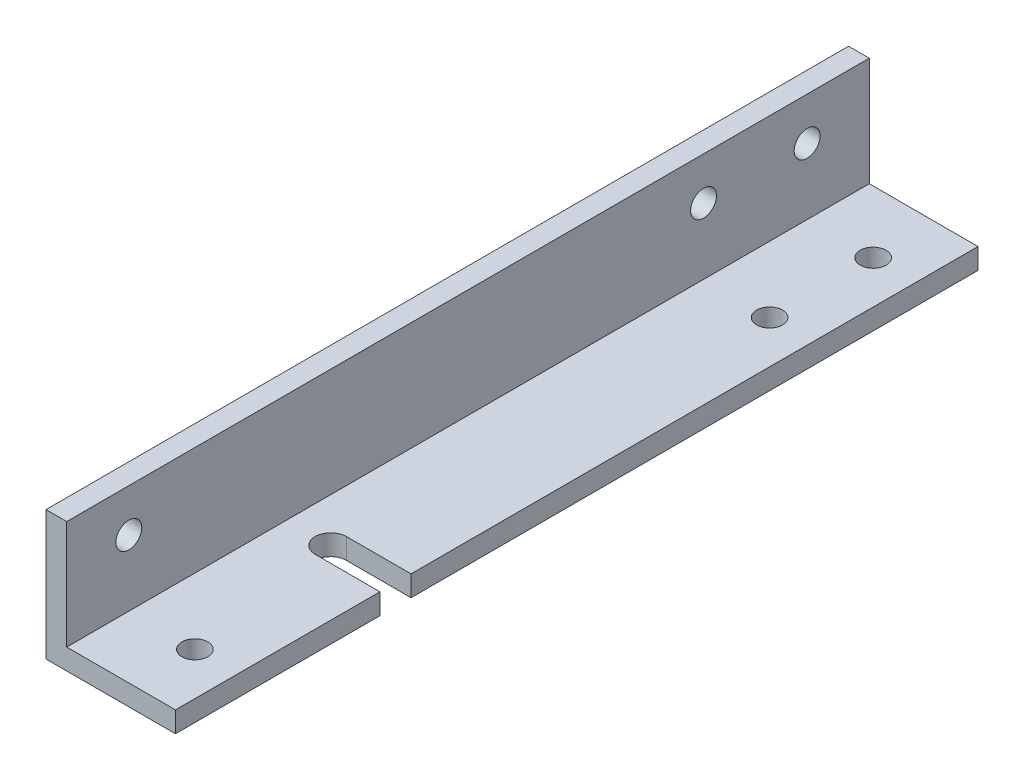
SolidWorks part; units mm, degrees
ref_plane "前视基准面" through (0, 0, 0) normal (0, 0, 1) x (1, 0, 0)
ref_plane "上视基准面" through (0, 0, 0) normal (0, 1, 0) x (1, 0, 0)
ref_plane "右视基准面" through (0, 0, 0) normal (1, 0, 0) x (0, 0, -1)
sketch "草图1" plane through (0, 0, 0) normal (0, 0, 1) x (1, 0, 0)
  line L0 (0, 25) -> (0, 0)
  line L1 (0, 0) -> (25, 0)
  line L2 (25, 0) -> (25, 4)
  line L3 (25, 4) -> (4, 4)
  line L4 (4, 4) -> (4, 25)
  line L5 (4, 25) -> (0, 25)
  dimension "D1" = 4
  dimension "D2" = 25
extrude "凸台-拉伸1" add sketch "草图1" along normal blind 155
hole_wizard "M6 螺纹孔1" positions "草图2" profile "草图3" tap size "M6" standard "GB" end condition through all
sketch "草图2" plane through (0, 4, 0) normal (0, 1, 0) x (1, 0, 0)
  line L0 (25, -155) -> (25, 0) construction
  line L1 (25, -155) -> (4, -155) construction
  line L2 (25, 0) -> (4, 0) construction
  line L3 (16.75, -12) -> (16.75, -32) construction
  point P0 (16.75, -12)
  point P2 (16.75, -143)
  point P12 (16.75, -32)
  dimension "D1" = 8.25
  dimension "D2" = 12
  dimension "D3" = 12
  dimension "D4" = 20
sketch "草图3" plane through (16.75, 4, 12) normal (1, 0, 0) x (0, 0, 1)
  line L0 (0, 0) -> (0, 4)
  line L1 (0, 4) -> (2.5, 4)
  line L2 (2.5, 4) -> (2.5, 0)
  line L5 (2.5, 0) -> (0, 0)
  line L11 (0, -6.35) -> (0, 107.95) construction
  dimension "通孔螺纹孔钻头直径" = 5
  dimension "通孔螺纹孔钻头深度" = 4
hole_wizard "M6 螺纹孔2" positions "草图4" profile "草图5" tap size "M6" standard "GB" end condition through all
sketch "草图4" plane through (4, 0, 0) normal (1, 0, 0) x (0, 0, -1)
  line L0 (-155, 25) -> (0, 25) construction
  line L1 (-155, 4) -> (-155, 25) construction
  line L2 (0, 4) -> (0, 25) construction
  line L3 (-32, 16.75) -> (-12, 16.75) construction
  point P0 (-143, 16.75)
  point P2 (-12, 16.75)
  point P12 (-32, 16.75)
  dimension "D1" = 8.25
  dimension "D2" = 12
  dimension "D3" = 12
  dimension "D4" = 20
sketch "草图5" plane through (4, 16.75, 143) normal (0, 1, 0) x (0, 0, -1)
  line L0 (0, 0) -> (0, 4)
  line L1 (0, 4) -> (2.5, 4)
  line L2 (2.5, 4) -> (2.5, 0)
  line L5 (2.5, 0) -> (0, 0)
  line L11 (0, -6.35) -> (0, 107.95) construction
  dimension "通孔螺纹孔钻头直径" = 5
  dimension "通孔螺纹孔钻头深度" = 4
sketch "草图6" plane through (0, 0, 0) normal (0, -1, 0) x (1, 0, 0)
  line L0 (25, 112.5) -> (12.5, 112.5) construction
  line L1 (25, 155) -> (25, 0) construction
  line L2 (25, 109.5) -> (12.5, 109.5)
  line L3 (25, 115.5) -> (12.5, 115.5)
  line L4 (0, 155) -> (25, 155) construction
  arc A0 (25, 109.5) -> (25, 115.5) centre (25, 112.5) ccw
  arc A1 (12.5, 115.5) -> (12.5, 109.5) centre (12.5, 112.5) ccw
  point P4 (18.75, 112.5)
  dimension "D1" = 3
  dimension "D2" = 12.5
  dimension "D3" = 42.5
extrude "切除-拉伸1" cut sketch "草图6" against normal through all
